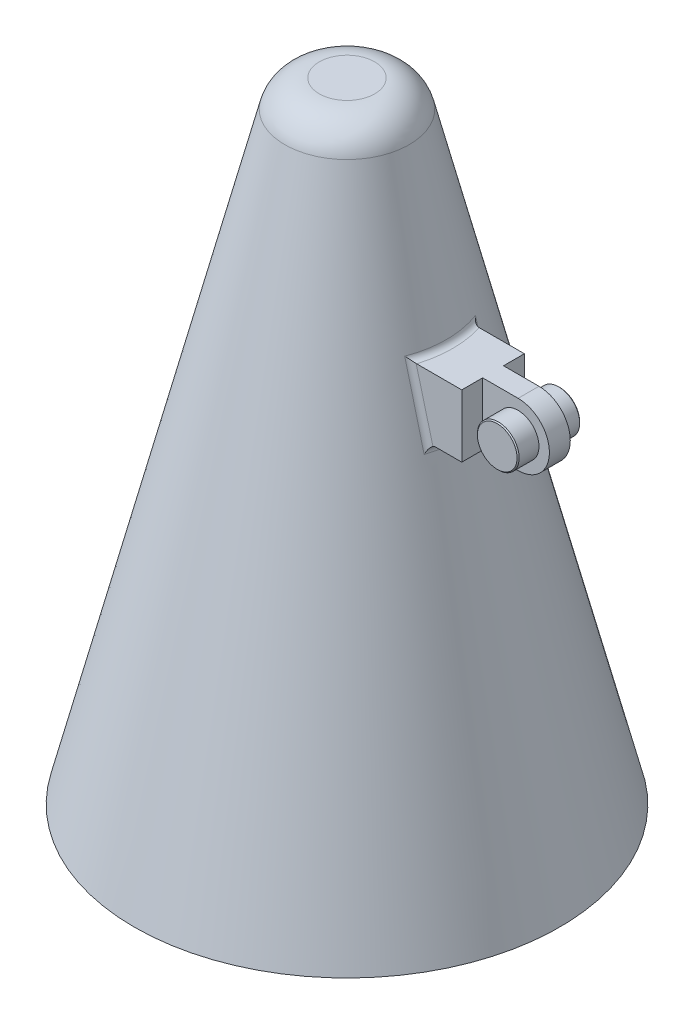
SolidWorks part; units mm, degrees
ref_plane "Front Plane" through (0, 0, 0) normal (0, 0, 1) x (1, 0, 0)
ref_plane "Top Plane" through (0, 0, 0) normal (0, 1, 0) x (1, 0, 0)
ref_plane "Right Plane" through (0, 0, 0) normal (1, 0, 0) x (0, 0, -1)
sketch "Sketch2" plane through (0, 0, 0) normal (0, 0, 1) x (1, 0, 0)
  line L0 (0, 0) -> (0, 300) construction
  line L1 (0, 300) -> (-13.2884, 300)
  line L2 (-27.8405, 288.638) -> (-100, 0)
  line L3 (-100, 0) -> (0, 0) construction
  arc A0 (-27.8405, 288.638) -> (-13.2884, 300) centre (-13.2884, 285) cw
  point P7 (-25, 300)
  dimension "D4" = 15
  dimension "D1" = 300
  dimension "D2" = 50
  dimension "D3" = 200
revolve "Revolve-Thin1" add sketch "Sketch2" angle 360 about L0
sketch "Sketch3" plane through (0, 0, 0) normal (1, 0, 0) x (0, 0, -1)
  line L0 (0, 200) -> (0, 0) construction
  line L1 (-15, 215) -> (15, 215)
  line L2 (-15, 215) -> (-15, 185)
  line L3 (-15, 185) -> (15, 185)
  line L4 (15, 215) -> (15, 185)
  line L5 (-15, 215) -> (15, 185) construction
  line L6 (-15, 185) -> (15, 215) construction
  point P0 (0, 200)
  dimension "D1" = 30
  dimension "D2" = 200
extrude "Boss-Extrude1" add sketch "Sketch3" against normal up to next from offset 70
sketch "Sketch4" plane through (0, 0, 0) normal (0, 0, 1) x (1, 0, 0)
  line L0 (70, 215) -> (87, 215)
  line L1 (87, 185) -> (70, 185)
  line L2 (70, 185) -> (70, 215)
  arc A0 (87, 215) -> (87, 185) centre (87, 200) cw
  dimension "D1" = 17
extrude "Boss-Extrude2" add sketch "Sketch4" along normal mid plane 10
sketch "Sketch5" plane through (0, 0, 0) normal (0, 0, 1) x (1, 0, 0)
  circle A0 centre (87, 200) radius 10
  dimension "D1" = 20
extrude "Boss-Extrude3" add sketch "Sketch5" along normal mid plane 30
fillet "Fillet1" radius 3 4 edges at (55.8116, 185, 0) (48.3116, 215, 0)
chamfer "Chamfer1" distance 0.5 angle 45 2 edges at (97, 200, -15) (97, 200, 15)
sketch "Sketch6" plane through (0, 0, 0) normal (0, 0, 1) x (1, 0, 0)
  line L0 (0, 200) -> (0, 250) construction
  line L2 (0, 200) -> (87, 200) construction
  line L3 (0, 250) -> (0, 300) construction
  line L4 (-13.2884, 300) -> (13.2884, 300) construction
  line L5 (0, 200) -> (0, 150) construction
  line L6 (0, 150) -> (0, 100) construction
  point P0 (0, 250)
  point P5 (0, 200)
  point P13 (0, 150)
  point P14 (0, 100)
